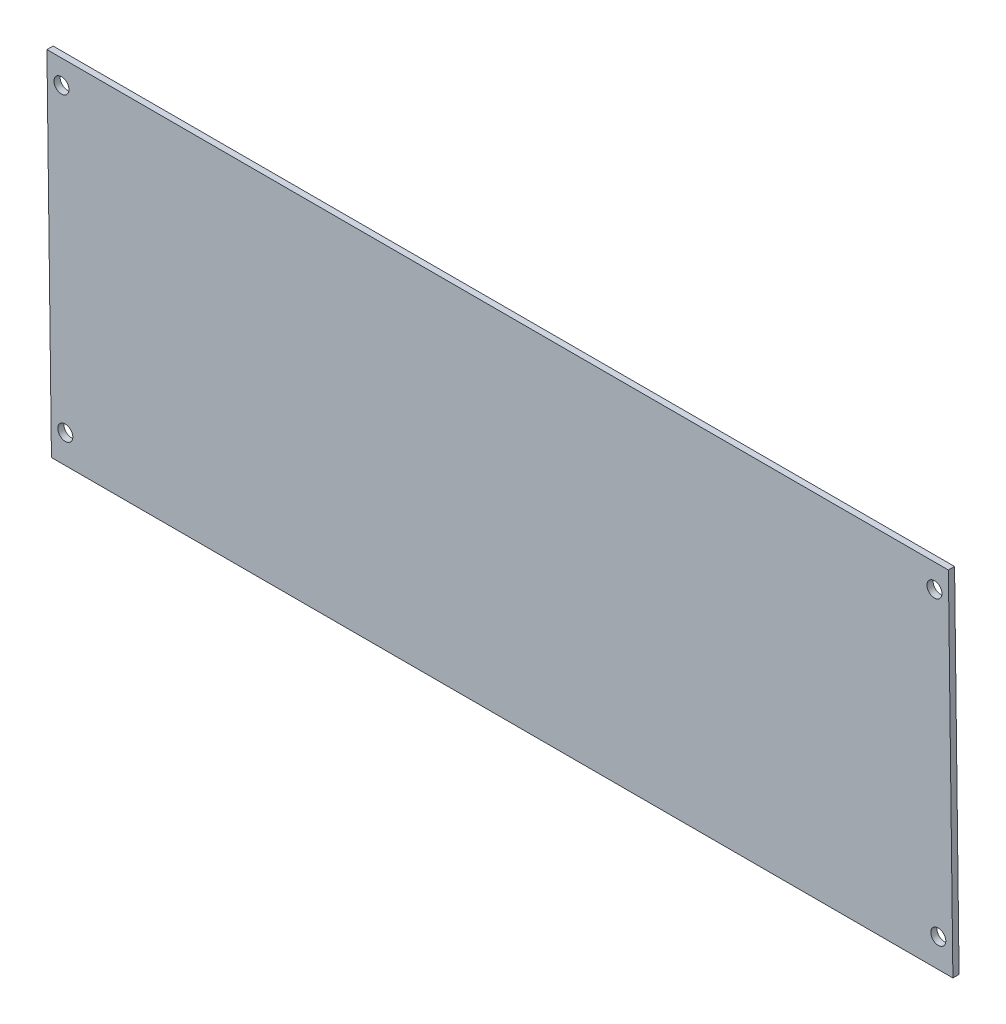
SolidWorks part; units mm, degrees
ref_plane "Alzado" through (0, 0, 0) normal (0, 0, 1) x (1, 0, 0)
ref_plane "Planta" through (0, 0, 0) normal (0, 1, 0) x (1, 0, 0)
ref_plane "Vista lateral" through (0, 0, 0) normal (1, 0, 0) x (0, 0, -1)
sketch "Sketch1" plane through (0, 0, 0) normal (0, 0, 1) x (1, 0, 0)
  line L0 (-3.5, 110.115) -> (-1, 110.115)
  line L1 (0, 32.1214) -> (190, 32.1214)
  line L2 (0, 32.1214) -> (-1, 110.115)
  line L4 (190, 32.1214) -> (189, 110.1214)
  line L14 (-3.5, 110.115) -> (-3.5, 115.115)
  line L15 (-3.5, 115.115) -> (191.5, 115.115)
  line L16 (191.5, 110.115) -> (191.5, 115.115)
  line L18 (189, 110.1214) -> (191.5, 110.115)
extrude "Boss-Extrude1" add sketch "Sketch1" along normal blind 1.3
sketch "Sketch3" plane through (0, 0, 1.3) normal (0, 0, 1) x (1, 0, 0)
  line L3 (191.5, 115.115) -> (-3.5, 115.115) construction
  line L4 (190, 32.1214) -> (189, 110.1214) construction
  line L5 (-1, 110.115) -> (0, 32.1214) construction
  line L6 (0, 32.1214) -> (190, 32.1214) construction
  circle A0 centre (186.0639, 105.115) radius 1.585
  circle A2 centre (2.0644, 105.115) radius 1.585
  circle A3 centre (2.872, 42.1214) radius 1.585
  circle A4 centre (186.8715, 42.1214) radius 1.585
  dimension "D2" = 3.17
  dimension "D4" = 3.17
  dimension "D5" = 3
  dimension "D6" = 10
  dimension "D9" = 3.17
  dimension "D8" = 3
  dimension "D10" = 10
  dimension "D11" = 3.17
  dimension "D1" = 10
  dimension "D3" = 3
  dimension "D7" = 10
  dimension "D12" = 3
ref_plane "Plane5" through (92.8885, 1.1909, 0) normal (0.9999, 0.0128, 0) x (0, 0, -1)
extrude "Cut-Extrude4" cut sketch "Sketch3" against normal blind 5
ref_plane "Plane6" through (0, 110.115, 0) normal (0, 1, 0) x (1, 0, 0)
sketch "Sketch8" plane through (0, 110.115, 0) normal (0, 1, 0) x (1, 0, 0)
  line L1 (-3.5, 0) -> (191.5, 0)
  line L2 (-3.5, 0) -> (-3.5, -1.3)
  line L3 (-3.5, -1.3) -> (191.5, -1.3)
  line L4 (191.5, 0) -> (191.5, -1.3)
extrude "Cut-Extrude5" cut sketch "Sketch8" along normal blind 10
ref_plane "Plane7" through (0, 35.1214, 0) normal (0, -1, 0) x (-1, 0, 0)
sketch "Sketch9" plane through (0, 35.1214, 0) normal (0, -1, 0) x (-1, 0, 0)
  line L1 (-190, 0) -> (1, 0)
  line L2 (-190, 0) -> (-190, -1.3)
  line L3 (-190, -1.3) -> (1, -1.3)
  line L4 (1, 0) -> (1, -1.3)
extrude "Cut-Extrude6" cut sketch "Sketch9" against normal blind 1 and the other way blind 3
